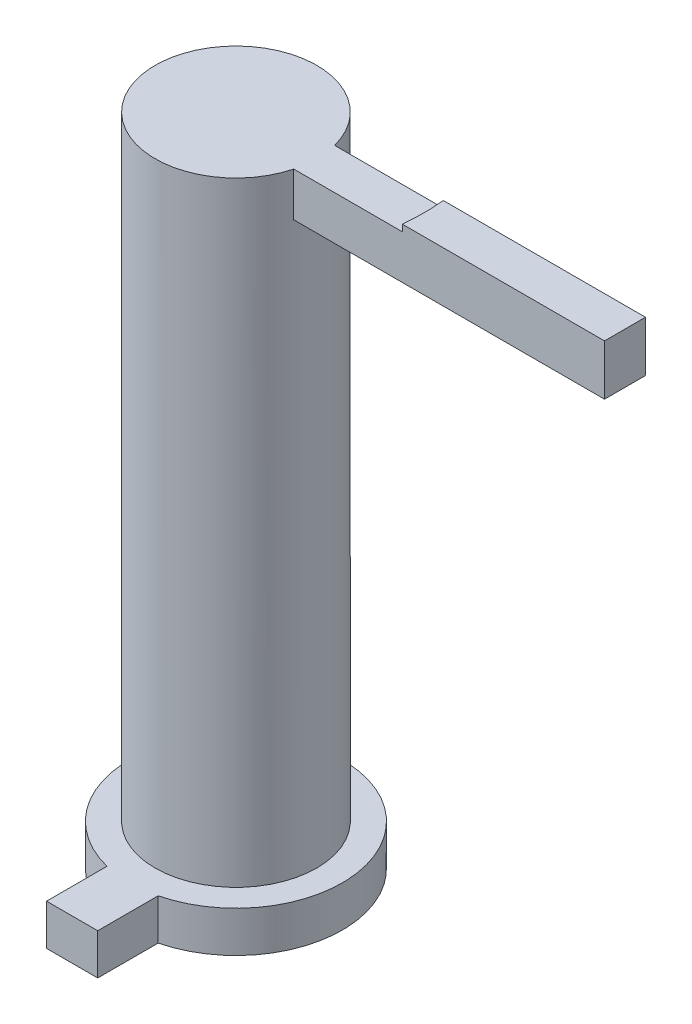
SolidWorks part; units mm, degrees
ref_plane "Front Plane" through (0, 0, 0) normal (0, 0, 1) x (1, 0, 0)
ref_plane "Top Plane" through (0, 0, 0) normal (0, 1, 0) x (1, 0, 0)
ref_plane "Right Plane" through (0, 0, 0) normal (1, 0, 0) x (0, 0, -1)
sketch "Sketch1" plane through (0, 0, 0) normal (0, 1, 0) x (1, 0, 0)
  circle A0 centre (0, 0) radius 3.95
extrude "Boss-Extrude1" add sketch "Sketch1" along normal blind 30
sketch "Sketch2" plane through (0, 0, 0) normal (0, -1, 0) x (1, 0, 0)
  circle A0 centre (0, 0) radius 5.2
  circle A1 centre (0, 0) radius 3.95 construction
  dimension "D1" = 1.25
extrude "Boss-Extrude2" add sketch "Sketch2" along normal blind 2
sketch "Sketch5" plane through (0, 0, 0) normal (1, 0, 0) x (0, 0, -1)
  line L1 (-1, 30.3213) -> (1, 30.3213)
  line L2 (-1, 30.3213) -> (-1, 27.8536)
  line L3 (-1, 27.8536) -> (1, 27.8536)
  line L4 (1, 30.3213) -> (1, 27.8536)
  line L6 (3.95, 0) -> (3.95, 30) construction
  point P4 (-1.0086, 30.3375)
  dimension "D1" = 2
  dimension "D2" = 2.95
extrude "Boss-Extrude3" add sketch "Sketch5" along normal blind 19
sketch "Sketch6" plane through (0, 30, 0) normal (0, 1, 0) x (1, 0, 0)
  circle A0 centre (0, 0) radius 9.1777
extrude "Cut-Extrude1" cut sketch "Sketch6" along normal up to surface (0.3213 mm away) up to face at (9.5, 30.3213, 0)
sketch "Sketch8" plane through (0, 0, 0) normal (0, 0, 1) x (1, 0, 0)
  line L0 (5.2, 0) -> (-5.2, 0) construction
  line L1 (-1.25, 0) -> (1.25, 0)
  line L2 (-1.25, 0) -> (-1.25, -2)
  line L3 (-1.25, -2) -> (1.25, -2)
  line L4 (1.25, 0) -> (1.25, -2)
  line L5 (-5.2, -2) -> (5.2, -2) construction
  dimension "D1" = 1.25
  dimension "D2" = 1.25
extrude "Boss-Extrude4" add sketch "Sketch8" along normal blind 8
